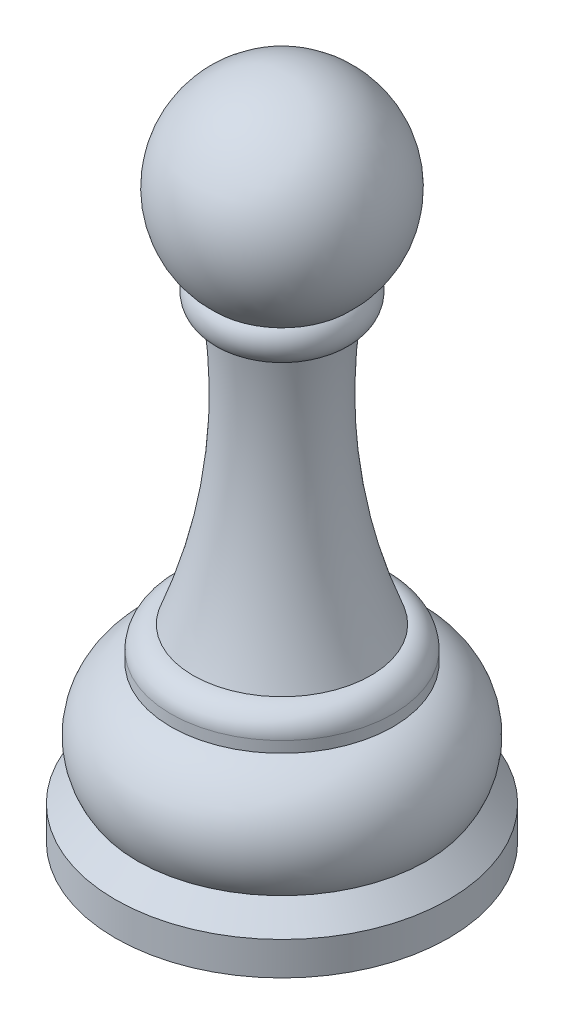
SolidWorks part; units mm, degrees
ref_plane "Ön Düzlem" through (0, 0, 0) normal (0, 0, 1) x (1, 0, 0)
ref_plane "Üst Düzlem" through (0, 0, 0) normal (0, 1, 0) x (1, 0, 0)
ref_plane "Sağ Düzlem" through (0, 0, 0) normal (1, 0, 0) x (0, 0, -1)
sketch "Çizim1" plane through (0, 0, 0) normal (0, 0, 1) x (1, 0, 0)
  line L0 (0, 102.3412) -> (0, -17.4955) construction
  line L1 (0, 0) -> (-15, 0)
  line L2 (-15, 0) -> (-15, 3)
  line L3 (-15, 3) -> (-13, 5)
  line L7 (-10, 13.97) -> (-10, 14.97)
  line L10 (0, 60.0182) -> (0, 0)
  arc A0 (-10, 13.97) -> (-13, 5) centre (-7.9981, 8.3138) ccw
  arc A1 (-10, 14.97) -> (-8, 16.97) centre (-8, 14.97) cw
  arc A2 (0, 60.0182) -> (-6, 44.31) centre (0, 51.0182) ccw
  arc A3 (-6, 44.31) -> (-4.9975, 41.05) centre (-4.5, 42.9871) ccw
  arc A4 (-4.9975, 41.05) -> (-8, 16.97) centre (-54.6316, 35.0115) cw
  dimension "D9" = 6
  dimension "D10" = 18
  dimension "D12" = 2
  dimension "D15" = 50
  dimension "D1" = 15
  dimension "D3" = 2
  dimension "D4" = 3
  dimension "D13" = 4.5
revolve "Döndür1" add sketch "Çizim1" angle 360 about L0
